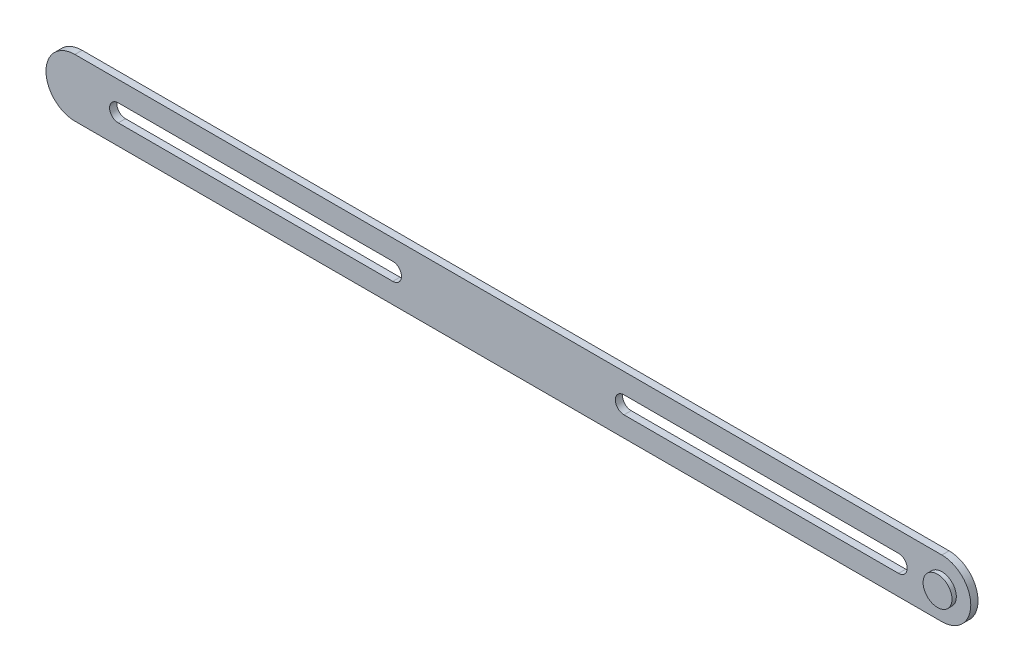
SolidWorks part; units mm, degrees
ref_plane "Front Plane" through (0, 0, 0) normal (0, 0, 1) x (1, 0, 0)
ref_plane "Top Plane" through (0, 0, 0) normal (0, 1, 0) x (1, 0, 0)
ref_plane "Right Plane" through (0, 0, 0) normal (1, 0, 0) x (0, 0, -1)
sketch "Sketch1" plane through (0, 0, 0) normal (0, 0, 1) x (1, 0, 0)
  circle A0 centre (0, 0) radius 2.5
  dimension "D1" = 5
extrude "Boss-Extrude1" add sketch "Sketch1" along normal blind 4
sketch "Sketch3" plane through (0, 0, 4) normal (0, 0, 1) x (1, 0, 0)
  line L0 (0, 0) -> (300, 0) construction
  line L1 (0, 10) -> (300, 10)
  line L2 (0, -10) -> (300, -10)
  line L3 (15, 0) -> (110, 0) construction
  line L4 (15, 3) -> (110, 3)
  line L5 (15, -3) -> (110, -3)
  line L6 (150, 0) -> (150, 22.7191) construction
  line L7 (150, 22.7191) -> (150, 0) construction
  line L8 (150, 0) -> (150, -20.6936) construction
  line L9 (285, 0) -> (190, 0) construction
  line L10 (285, 3) -> (190, 3)
  line L11 (285, -3) -> (190, -3)
  arc A0 (0, 10) -> (0, -10) centre (0, 0) ccw
  arc A1 (300, -10) -> (300, 10) centre (300, 0) ccw
  arc A2 (15, 3) -> (15, -3) centre (15, 0) ccw
  arc A3 (110, -3) -> (110, 3) centre (110, 0) ccw
  arc A5 (285, 3) -> (285, -3) centre (285, 0) cw
  arc A6 (190, -3) -> (190, 3) centre (190, 0) cw
  circle A7 centre (0, 0) radius 2.5 construction
  point P3 (150, 0)
  point P10 (62.5, 0)
  point P22 (237.5, 0)
  dimension "D2" = 10
  dimension "D5" = 3
  dimension "D1" = 300
  dimension "D3" = 95
  dimension "D4" = 15
extrude "Boss-Extrude3" add sketch "Sketch3" along normal blind 2.5
sketch "Sketch5" plane through (0, 0, 4) normal (0, 0, -1) x (-1, 0, 0)
  circle A0 centre (-300, 0) radius 5
  dimension "D1" = 10
extrude "Boss-Extrude4" add sketch "Sketch5" along normal blind 3.5 and the other way blind 4
